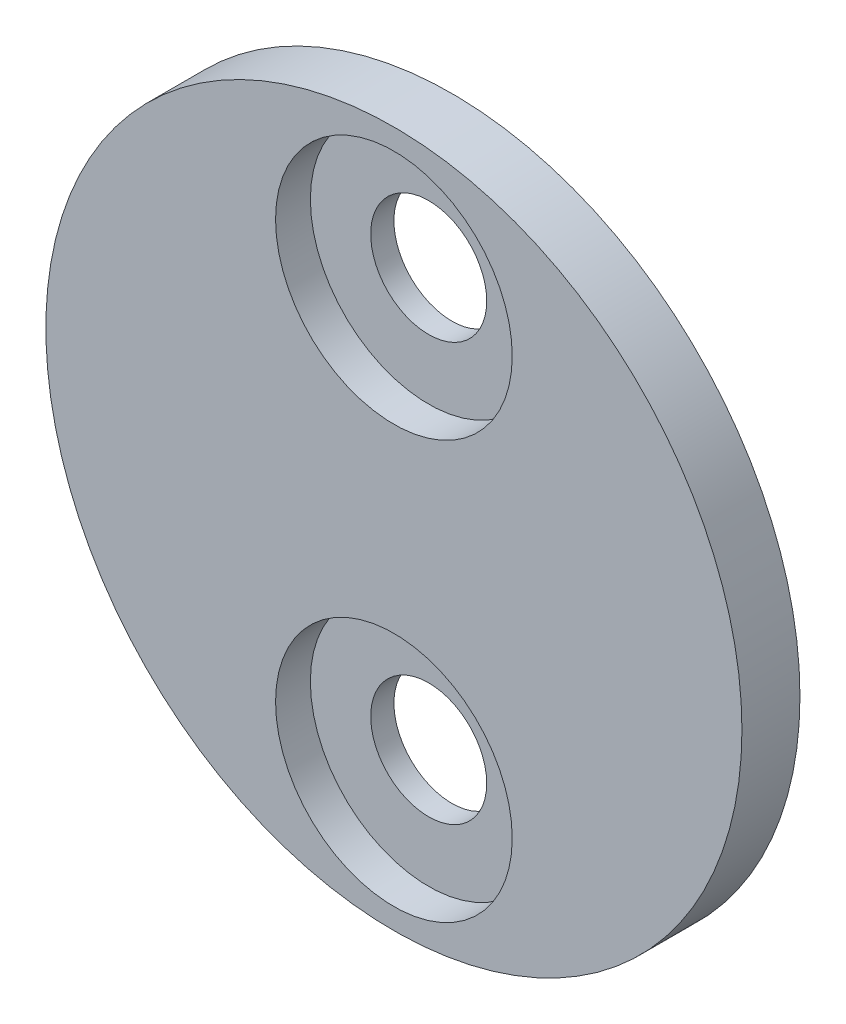
SolidWorks part; units mm, degrees
ref_plane "Front Plane" through (0, 0, 0) normal (0, 0, 1) x (1, 0, 0)
ref_plane "Top Plane" through (0, 0, 0) normal (0, 1, 0) x (1, 0, 0)
ref_plane "Right Plane" through (0, 0, 0) normal (1, 0, 0) x (0, 0, -1)
sketch "Sketch2" plane through (0, 0, 0) normal (0, 0, 1) x (1, 0, 0)
  circle A0 centre (0, 0) radius 2.4
  dimension "D1" = 4.8
extrude "Boss-Extrude1" add sketch "Sketch2" along normal blind 6
sketch "Sketch3" plane through (0, 0, 6) normal (0, 0, 1) x (1, 0, 0)
  circle A0 centre (0, 0) radius 15
  dimension "D1" = 30
extrude "Boss-Extrude2" add sketch "Sketch3" along normal blind 2.5
fillet "Fillet1" radius 2 1 edges at (2.4, 0, 6)
sketch "Sketch4" plane through (0, 0, 8.5) normal (0, 0, 1) x (1, 0, 0)
  line L0 (0, -15) -> (0, 15)
  circle A0 centre (0, 0) radius 15 construction
  circle A1 centre (0, 9) radius 5.1
  circle A2 centre (0, -9) radius 5.1
  point P0 (0, 9)
  point P7 (0, 0)
  point P9 (0, -9)
  dimension "D1" = 10.2
  dimension "D4" = 10.2
  dimension "D2" = 6
  dimension "D3" = 6
extrude "Cut-Extrude1" cut sketch "Sketch4" against normal blind 1.5 contours L0 A1 | L0 A1 | L0 A2 | L0 A2
sketch "Sketch5" plane through (0, 0, 7) normal (0, 0, 1) x (1, 0, 0)
  circle A0 centre (0, -9) radius 2.5
  circle A1 centre (0, 9) radius 2.5
  dimension "D1" = 5
  dimension "D2" = 5
extrude "Cut-Extrude2" cut sketch "Sketch5" against normal through all
chamfer "Chamfer1" distance 0.5 angle 50 1 edges at (2.4, 0, 0)
